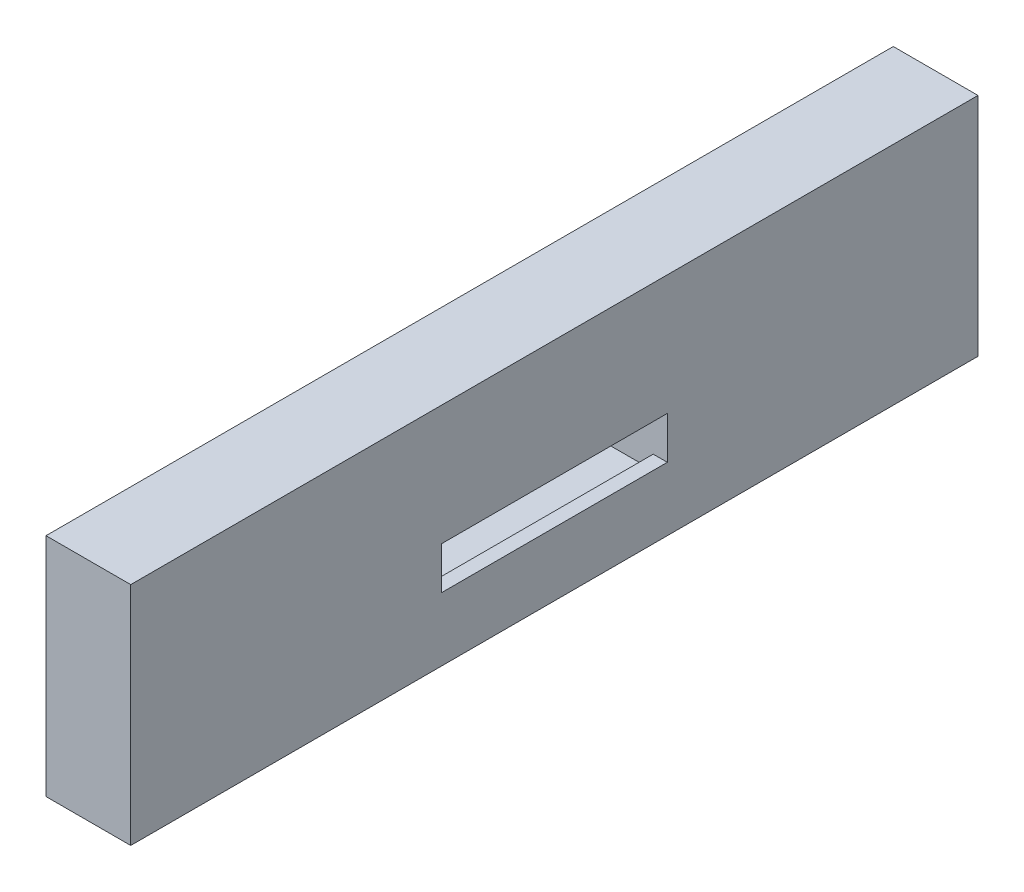
SolidWorks part; units mm, degrees
ref_plane "Front Plane" through (0, 0, 0) normal (0, 0, 1) x (1, 0, 0)
ref_plane "Top Plane" through (0, 0, 0) normal (0, 1, 0) x (1, 0, 0)
ref_plane "Right Plane" through (0, 0, 0) normal (1, 0, 0) x (0, 0, -1)
sketch "Sketch1" plane through (0, 0, 0) normal (1, 0, 0) x (0, 0, -1)
  line L1 (0, 0) -> (762, 0)
  line L2 (0, 0) -> (0, 203.2)
  line L3 (0, 203.2) -> (762, 203.2)
  line L4 (762, 0) -> (762, 203.2)
  dimension "D1" = 762
  dimension "D2" = 203.2
extrude "Boss-Extrude1" add sketch "Sketch1" along normal blind 76.2
sketch "Sketch2" plane through (0, 0, 0) normal (-1, 0, 0) x (0, 0, 1)
  line L1 (-482.6, 44.45) -> (-279.4, 44.45)
  line L2 (-482.6, 44.45) -> (-482.6, 139.7)
  line L3 (-482.6, 139.7) -> (-279.4, 139.7)
  line L4 (-279.4, 44.45) -> (-279.4, 139.7)
  line L6 (0, 0) -> (-762, 0) construction
  line L7 (-762, 0) -> (-762, 203.2) construction
  point P6 (-381, 139.7)
  dimension "D1" = 44.45
  dimension "D2" = 381
  dimension "D3" = 95.25
  dimension "D4" = 203.2
extrude "Cut-Extrude1" cut sketch "Sketch2" against normal blind 63.5
sketch "Sketch3" plane through (63.5, 0, 0) normal (-1, 0, 0) x (0, 0, 1)
  line L0 (-279.4, 44.45) -> (-279.4, 139.7) construction
  line L1 (-482.6, 95.25) -> (-279.4, 95.25)
  line L2 (-482.6, 95.25) -> (-482.6, 57.15)
  line L3 (-482.6, 57.15) -> (-279.4, 57.15)
  line L4 (-279.4, 95.25) -> (-279.4, 57.15)
  line L5 (-482.6, 44.45) -> (-279.4, 44.45) construction
  line L6 (-482.6, 139.7) -> (-482.6, 44.45) construction
  point P9 (-482.6, 139.7)
  point P10 (0, 0)
  point P11 (-487.5529, 109.9214)
  dimension "D1" = 12.7
  dimension "D2" = 38.1
extrude "Cut-Extrude2" cut sketch "Sketch3" against normal through all
fillet "Fillet1" radius 25.4 2 edges at (31.75, 139.7, -279.4) (31.75, 139.7, -482.6)
